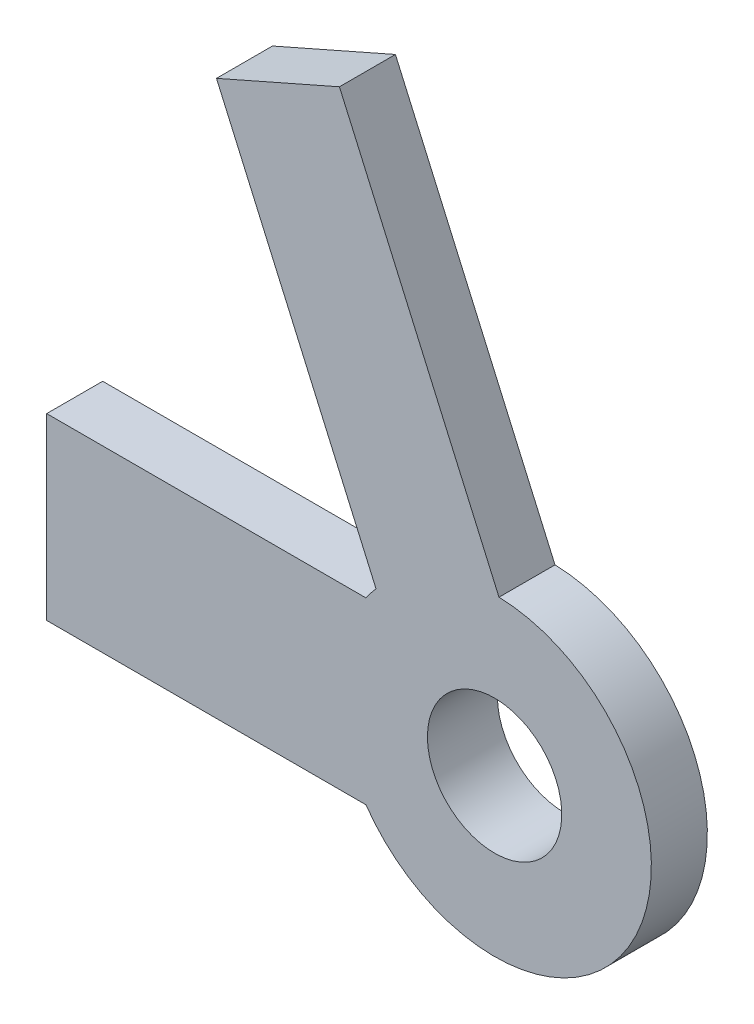
SolidWorks part; units mm, degrees
ref_plane "Plan de face" through (0, 0, 0) normal (0, 0, 1) x (1, 0, 0)
ref_plane "Plan de dessus" through (0, 0, 0) normal (0, 1, 0) x (1, 0, 0)
ref_plane "Plan de droite" through (0, 0, 0) normal (1, 0, 0) x (0, 0, -1)
sketch "Esquisse1" plane through (0, 0, 0) normal (0, 0, 1) x (1, 0, 0)
  line L0 (0, 0) -> (-12.2228, 27.7521) construction
  line L1 (-25.7446, 0) -> (0, 0) construction
  line L4 (-24.8382, 41.5098) -> (-10.5895, 9.1577)
  line L5 (-24.8382, 41.5098) -> (-13.8562, 46.3466)
  line L6 (-10.5895, 9.1577) -> (0.3926, 13.9945)
  line L7 (-13.8562, 46.3466) -> (0.3926, 13.9945)
  line L8 (-24.8382, 41.5098) -> (0.3926, 13.9945) construction
  line L9 (-10.5895, 9.1577) -> (-13.8562, 46.3466) construction
  line L10 (-40, 8) -> (-11.4891, 8)
  line L11 (-40, 8) -> (-40, -8)
  line L12 (-11.4891, 8) -> (-11.4891, -8)
  line L13 (-40, -8) -> (-11.4891, -8)
  line L14 (-40, 8) -> (-11.4891, -8) construction
  line L15 (-11.4891, 8) -> (-40, -8) construction
  circle A0 centre (0, 0) radius 14
  point P3 (0, 0)
  point P6 (0, 0)
  point P7 (1.7176, 13.8942)
  point P16 (0, 0)
  dimension "D1" = 28
  dimension "D2" = 66.23
  dimension "D3" = 48
  dimension "D4" = 12
  dimension "D5" = 16
  dimension "D6" = 40
extrude "Boss.-Extru.1" add sketch "Esquisse1" along normal mid plane 5 contours L6 A0 L12 | L6 A0 | L12 A0 | A0 L10 L11 L13 | A0 L7 L5 L4
sketch "Esquisse2" plane through (0, 0, -2.5) normal (0, 0, -1) x (-1, 0, 0)
  circle A0 centre (0, 0) radius 10
  dimension "D1" = 20
extrude "Boss.-Extru.2" add sketch "Esquisse2" along normal mid plane 2.5 contours A0
sketch "Esquisse3" plane through (0, 0, -3.75) normal (0, 0, -1) x (-1, 0, 0)
  circle A0 centre (0, 0) radius 6
extrude "Enlèv. mat.-Extru.1" cut sketch "Esquisse3" against normal through all
